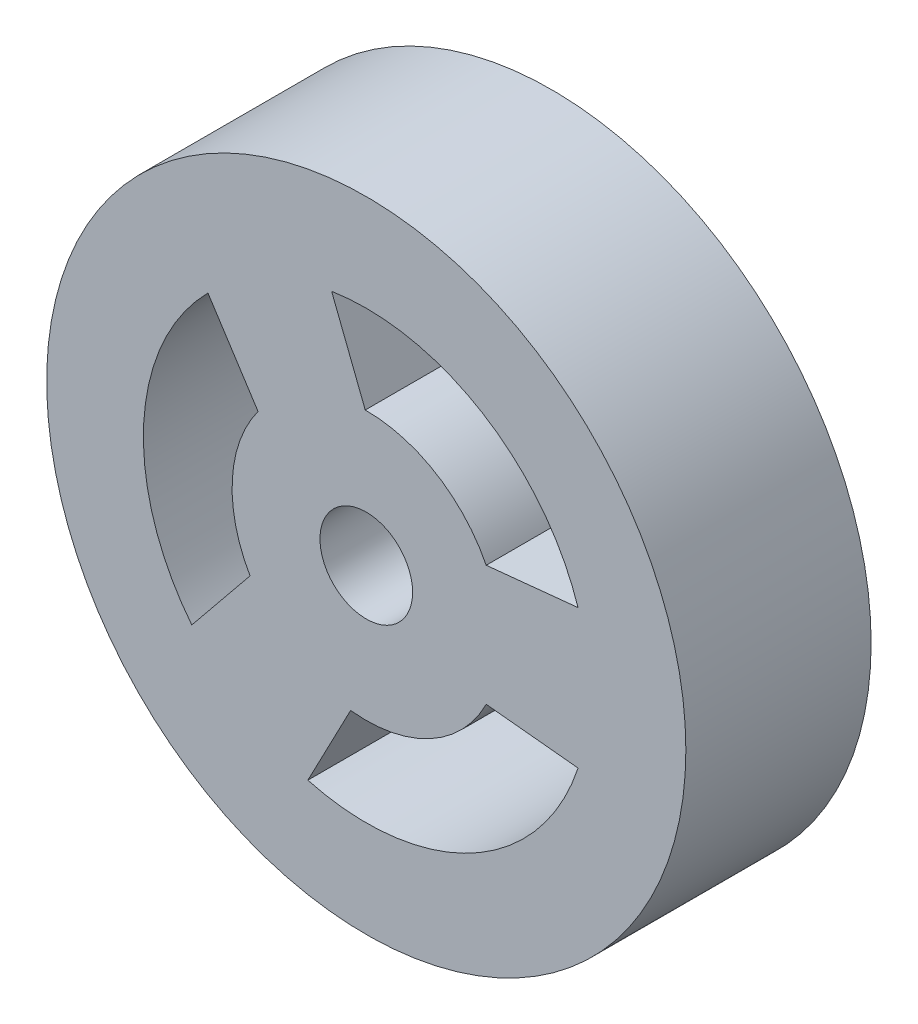
SolidWorks part; units mm, degrees
ref_plane "Front" through (0, 0, 0) normal (0, 0, 1) x (1, 0, 0)
ref_plane "Top" through (0, 0, 0) normal (0, 1, 0) x (1, 0, 0)
ref_plane "Right" through (0, 0, 0) normal (1, 0, 0) x (0, 0, -1)
sketch "Sketch1" plane through (0, 0, 0) normal (0, 0, 1) x (1, 0, 0)
  line L0 (268.439, -83.0806) -> (278.3553, -84.0806)
  line L1 (242.9468, -83.8194) -> (236.6592, -91.5524)
  line L2 (253.8054, -90.9673) -> (249.1883, -99.7999)
  line L5 (251.7556, -52.8125) -> (255.3829, -62.0956)
  line L6 (238.4025, -59.6459) -> (243.8102, -68.0179)
  line L7 (278.3553, -69.0806) -> (268.439, -70.0806)
  circle A0 centre (255.4938, -76.5806) radius 34.5
  arc A1 (238.4025, -59.6459) -> (236.6592, -91.5524) centre (255.4938, -76.5806) ccw
  arc A2 (243.8102, -68.0179) -> (242.9468, -83.8194) centre (255.4938, -76.5806) ccw
  arc A3 (253.8054, -90.9673) -> (268.439, -83.0806) centre (255.4938, -76.5806) ccw
  arc A4 (249.1883, -99.7999) -> (278.3553, -84.0806) centre (255.4938, -76.5806) ccw
  arc A5 (268.439, -70.0806) -> (255.3829, -62.0956) centre (255.4938, -76.5806) ccw
  arc A6 (278.3553, -69.0806) -> (251.7556, -52.8125) centre (255.4938, -76.5806) ccw
  circle A7 centre (255.4938, -76.5806) radius 5
  dimension "D7" = 69
  dimension "D8" = 10
  dimension "D1" = 13
  dimension "D2" = 13
  dimension "D3" = 13
  dimension "D4" = 15
  dimension "D5" = 15
  dimension "D6" = 15
extrude "Base-Extrude" add sketch "Sketch1" along normal blind 20
